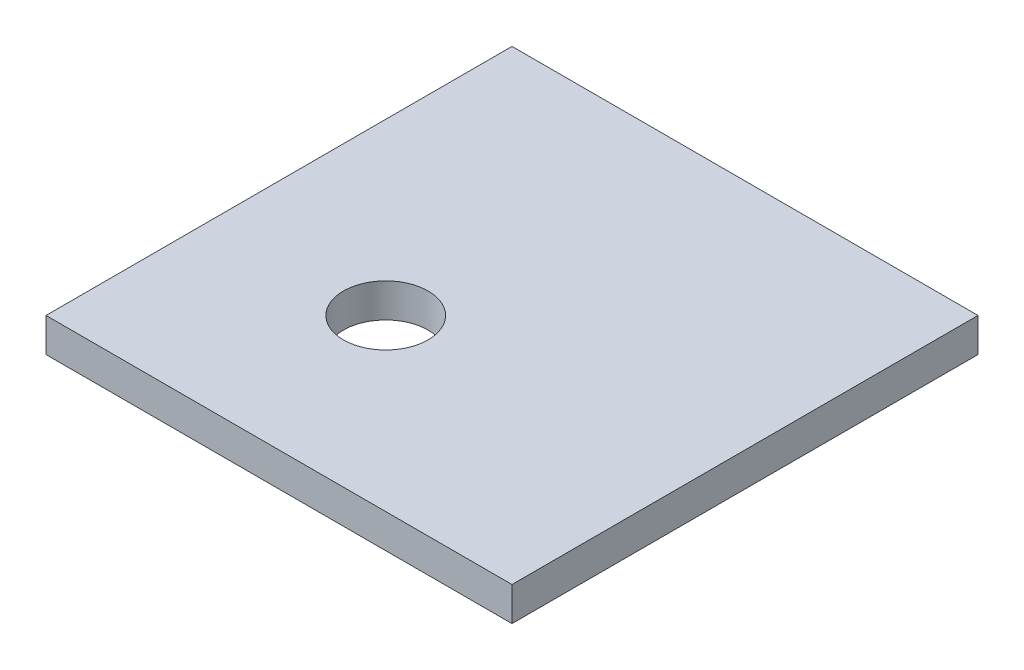
SolidWorks part; units mm, degrees
ref_plane "前视基准面" through (0, 0, 0) normal (0, 0, 1) x (1, 0, 0)
ref_plane "上视基准面" through (0, 0, 0) normal (0, 1, 0) x (1, 0, 0)
ref_plane "右视基准面" through (0, 0, 0) normal (1, 0, 0) x (0, 0, -1)
sketch "草图1" plane through (0, 0, 0) normal (0, 1, 0) x (1, 0, 0)
  line L1 (-49.4842, 35.1433) -> (60.5158, 35.1433)
  line L2 (-49.4842, 35.1433) -> (-49.4842, -74.8567)
  line L3 (-49.4842, -74.8567) -> (60.5158, -74.8567)
  line L4 (60.5158, 35.1433) -> (60.5158, -74.8567)
  dimension "D1" = 110
  dimension "D2" = 110
extrude "凸台-拉伸1" add sketch "草图1" along normal blind 8 contours L3 L4 L1 L2
sketch "草图6" plane through (0, 8, 0) normal (0, 1, 0) x (1, 0, 0)
  line L0 (60.5158, -74.8567) -> (-66.5518, 52.2108) construction
  line L1 (-49.4842, -74.8567) -> (71.447, 46.0745) construction
  circle A4 centre (-9.3866, -34.7591) radius 10
  dimension "D1" = 20
extrude "切除-拉伸1" cut sketch "草图6" against normal blind 8
